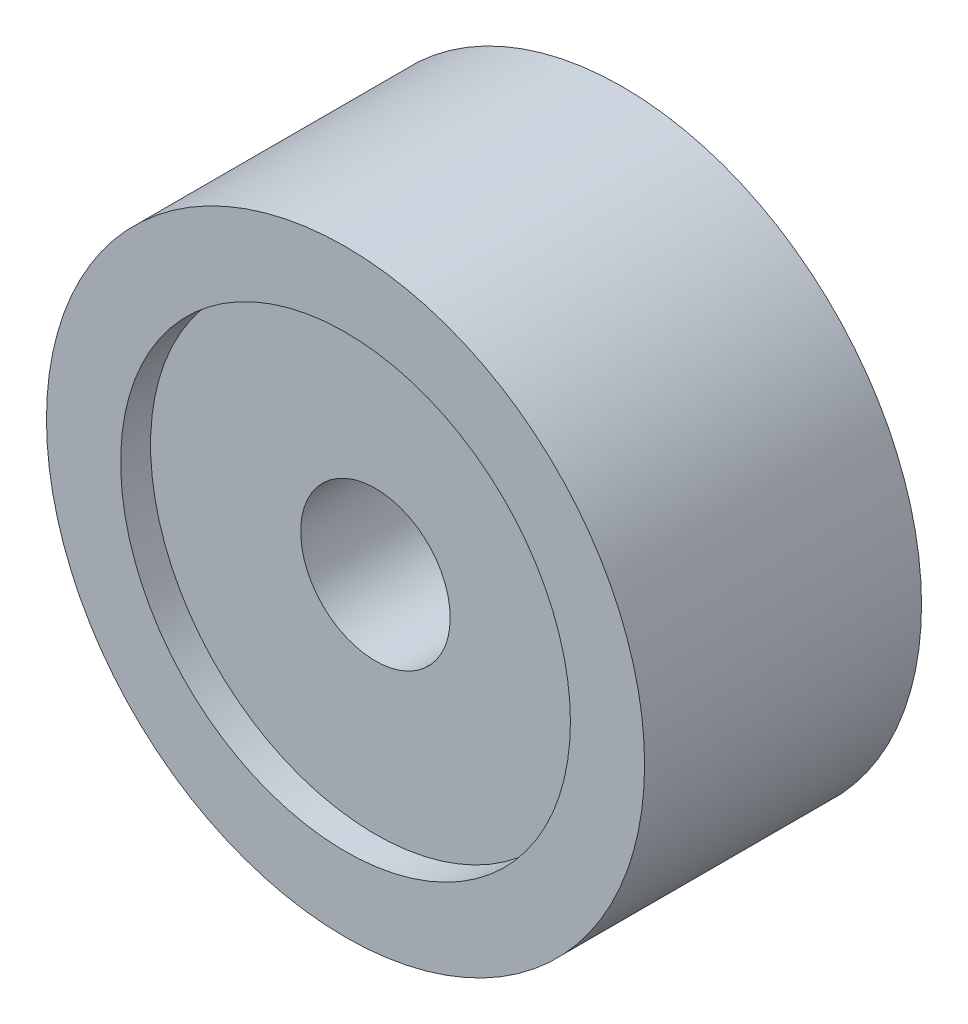
SolidWorks part; units mm, degrees
ref_plane "Front Plane" through (0, 0, 0) normal (0, 0, 1) x (1, 0, 0)
ref_plane "Top Plane" through (0, 0, 0) normal (0, 1, 0) x (1, 0, 0)
ref_plane "Right Plane" through (0, 0, 0) normal (1, 0, 0) x (0, 0, -1)
sketch "Sketch1" plane through (0, 0, 0) normal (0, 0, 1) x (1, 0, 0)
  circle A0 centre (0, 0) radius 3.175
  circle A1 centre (0, 0) radius 12.7
  dimension "ID" = 6.35
  dimension "OD" = 25.4
extrude "Extrude1" add sketch "Sketch1" against normal blind 11.7602
sketch "Sketch2" plane through (0, 0, 0) normal (0, 0, 1) x (1, 0, 0)
  circle A0 centre (0, 0) radius 9.55
extrude "Cut-Extrude1" cut sketch "Sketch2" against normal blind 1.27
